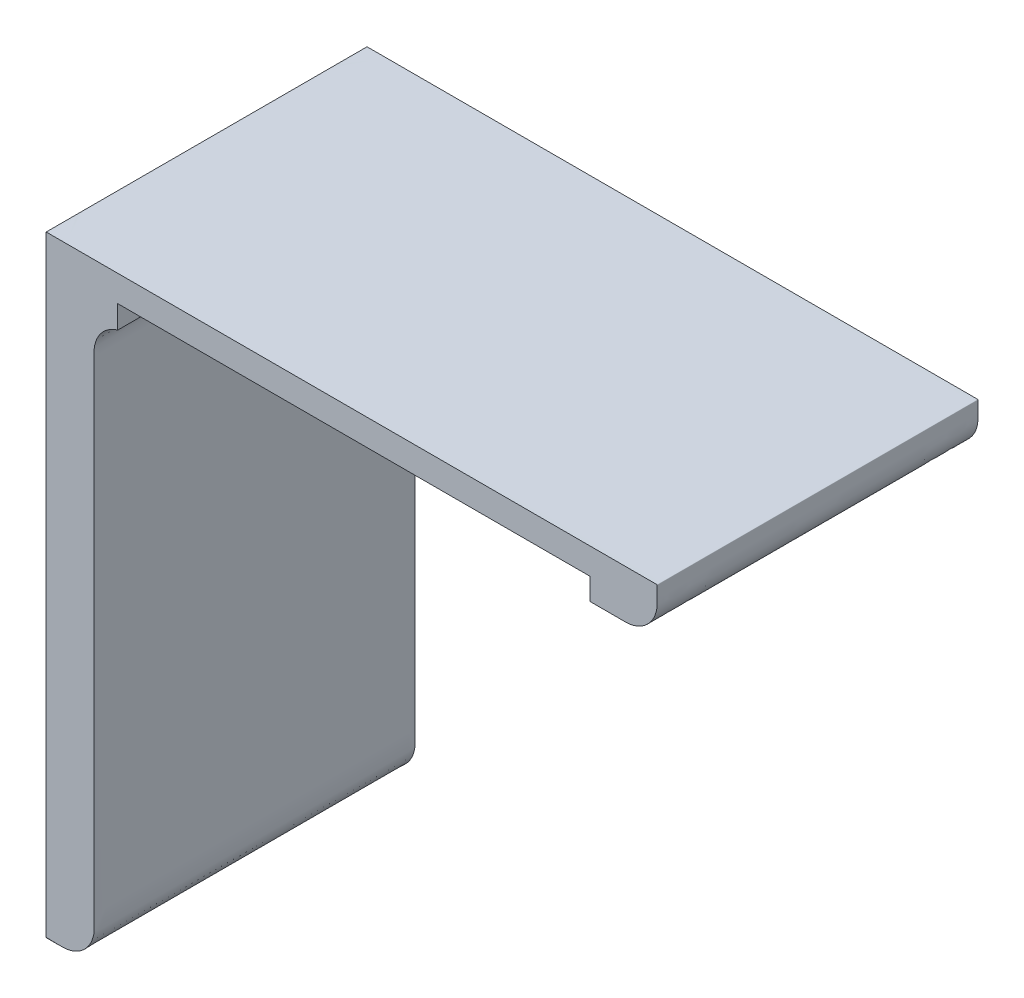
SolidWorks part; units mm, degrees
ref_plane "Alzado" through (0, 0, 0) normal (0, 0, 1) x (1, 0, 0)
ref_plane "Planta" through (0, 0, 0) normal (0, 1, 0) x (1, 0, 0)
ref_plane "Vista lateral" through (0, 0, 0) normal (1, 0, 0) x (0, 0, -1)
sketch "Croquis1" plane through (0, 0, 0) normal (0, 0, 1) x (1, 0, 0)
  line L0 (16.906, 15.906) -> (-14.194, 15.906) construction
  line L1 (-18.194, -19.194) -> (-19.194, -19.194) construction
  line L2 (18.906, 17.906) -> (18.906, 18.906) construction
  line L3 (18.906, 18.906) -> (-19.194, 18.906) construction
  line L4 (-19.194, -19.194) -> (-19.194, 18.906) construction
  line L5 (0, 0) -> (-19.194, 18.906) construction
  line L6 (18.906, 18.906) -> (-19.194, -19.194) construction
  line L7 (-16.194, -17.194) -> (-16.194, 13.906) construction
  line L8 (-16.194, -19.194) -> (-16.194, 15.906) construction
  line L9 (18.906, 15.906) -> (-16.194, 15.906) construction
  arc A0 (-18.194, -19.194) -> (-16.194, -17.194) centre (-18.194, -17.194) ccw construction
  arc A1 (-16.194, 13.906) -> (-14.194, 15.906) centre (-14.194, 13.906) cw construction
  arc A2 (18.906, 17.906) -> (16.906, 15.906) centre (16.906, 17.906) cw construction
  spline S0 degree 3 poles (18.906, 18.156) (18.906, 18.3978) (18.906, 18.6396) (18.906, 18.8815) (18.906, 18.8853) (18.906, 18.893) (18.893, 18.906) (18.8853, 18.906) (18.8815, 18.906) (6.1978, 18.906) (-6.4859, 18.906) (-19.1695, 18.906) (-19.1734, 18.906) (-19.1811, 18.906) (-19.194, 18.893) (-19.194, 18.8853) (-19.194, 18.8815) (-19.194, 6.1978) (-19.194, -6.4859) (-19.194, -19.1695) (-19.194, -19.1734) (-19.194, -19.1811) (-19.1811, -19.194) (-19.1734, -19.194) (-19.1695, -19.194) (-18.9277, -19.194) (-18.6859, -19.194) (-18.444, -19.194) (-18.4162, -19.194) (-18.3607, -19.194) (-18.2774, -19.194) (-18.2218, -19.194) (-18.194, -19.194) (-18.1661, -19.194) (-18.1102, -19.194) (-18.0264, -19.1876) (-17.9708, -19.1817) (-17.9431, -19.1782) (-17.2129, -19.0859) (-16.6279, -18.6393) (-16.3463, -17.9594) (-16.3131, -17.8793) (-16.2571, -17.7148) (-16.194, -17.4541) (-16.194, -17.2807) (-16.194, -17.194) (-16.194, -17.1073) (-16.194, -16.9339) (-16.194, -16.6738) (-16.194, -16.5004) (-16.194, -16.4137) (-16.194, -6.5672) (-16.194, 3.2792) (-16.194, 13.1256) (-16.194, 13.2123) (-16.194, 13.3857) (-16.194, 13.6459) (-16.194, 13.8193) (-16.194, 13.906) (-16.194, 13.9927) (-16.194, 14.1661) (-16.1309, 14.4267) (-16.075, 14.5912) (-16.0418, 14.6713) (-15.8361, 15.168) (-15.456, 15.548) (-14.9594, 15.7537) (-14.8793, 15.7869) (-14.7148, 15.8429) (-14.4541, 15.906) (-14.2807, 15.906) (-14.194, 15.906) (-14.1073, 15.906) (-13.9339, 15.906) (-13.6738, 15.906) (-13.5004, 15.906) (-13.4137, 15.906) (-3.5672, 15.906) (6.2792, 15.906) (16.1256, 15.906) (16.2123, 15.906) (16.3857, 15.906) (16.6459, 15.906) (16.8193, 15.906) (16.906, 15.906) (16.9927, 15.906) (17.1661, 15.906) (17.4267, 15.9691) (17.5912, 16.025) (17.6713, 16.0582) (18.3513, 16.3399) (18.7978, 16.9249) (18.8902, 17.655) (18.8937, 17.6827) (18.8995, 17.7383) (18.906, 17.8222) (18.906, 17.878) (18.906, 17.906) (18.906, 17.9338) (18.906, 17.9893) (18.906, 18.0726) (18.906, 18.1282) (18.906, 18.156) (18.906, 18.3978) (18.906, 18.6396) knots -0.000557 0 0 0 0.004852 0.004852 0.004852 0.004929 0.005006 0.005084 0.005084 0.005084 0.259555 0.259555 0.259555 0.259632 0.259709 0.259787 0.259787 0.259787 0.514258 0.514258 0.514258 0.514335 0.514412 0.51449 0.51449 0.51449 0.519341 0.519341 0.519341 0.519899 0.520456 0.521013 0.521013 0.521013 0.521574 0.522134 0.522695 0.522695 0.522695 0.536129 0.536129 0.536129 0.537869 0.539608 0.541348 0.541348 0.541348 0.543088 0.544827 0.546567 0.546567 0.546567 0.744115 0.744115 0.744115 0.745854 0.747594 0.749333 0.749333 0.749333 0.751073 0.752813 0.754552 0.754552 0.754552 0.764789 0.764789 0.764789 0.766529 0.768268 0.770008 0.770008 0.770008 0.771748 0.773487 0.775227 0.775227 0.775227 0.972775 0.972775 0.972775 0.974514 0.976254 0.977994 0.977994 0.977994 0.979733 0.981473 0.983212 0.983212 0.983212 0.996646 0.996646 0.996646 0.997207 0.997768 0.998328 0.998328 0.998328 0.998885 0.999443 1 1 1 1.004852 1.004852 1.004852 weights 1 1 1 1 1 1 1 1 1 1 1 1 1 1 1 1 1 1 1 1 1 1 1 1 1 1 1 1 1 1 1 1 1 1 1 1 1 1 0.909833 0.909833 1 1 1 1 1 1 1 1 1 1 1 1 1 1 1 1 1 1 1 1 1 1 1 1 0.949253 0.949253 1 1 1 1 1 1 1 1 1 1 1 1 1 1 1 1 1 1 1 1 1 1 1 1 0.909833 0.909833 1 1 1 1 1 1 1 1 1 1 1 1 1 only from (18.906, 18.156) to (18.906, 18.156)
  point P0 (0, 0)
  dimension "D4" = 2
  dimension "D1" = 38.1
  dimension "D2" = 38.1
  dimension "D3" = 3
extrude "Saliente-Extruir1" add sketch "Croquis1" along normal blind 20
sketch "Croquis2" plane through (0, 0, 20) normal (0, 0, 1) x (1, 0, 0)
  line L1 (14.725, -17.2675) -> (-14.725, -17.2675)
  line L2 (14.725, -17.2675) -> (14.725, 17.2675)
  line L3 (14.725, 17.2675) -> (-14.725, 17.2675)
  line L4 (-14.725, -17.2675) -> (-14.725, 17.2675)
  line L5 (14.725, -17.2675) -> (-14.725, 17.2675) construction
  line L6 (14.725, 17.2675) -> (-14.725, -17.2675) construction
  point P0 (0, 0)
extrude "Cortar-Extruir1" cut sketch "Croquis2" against normal blind 43
